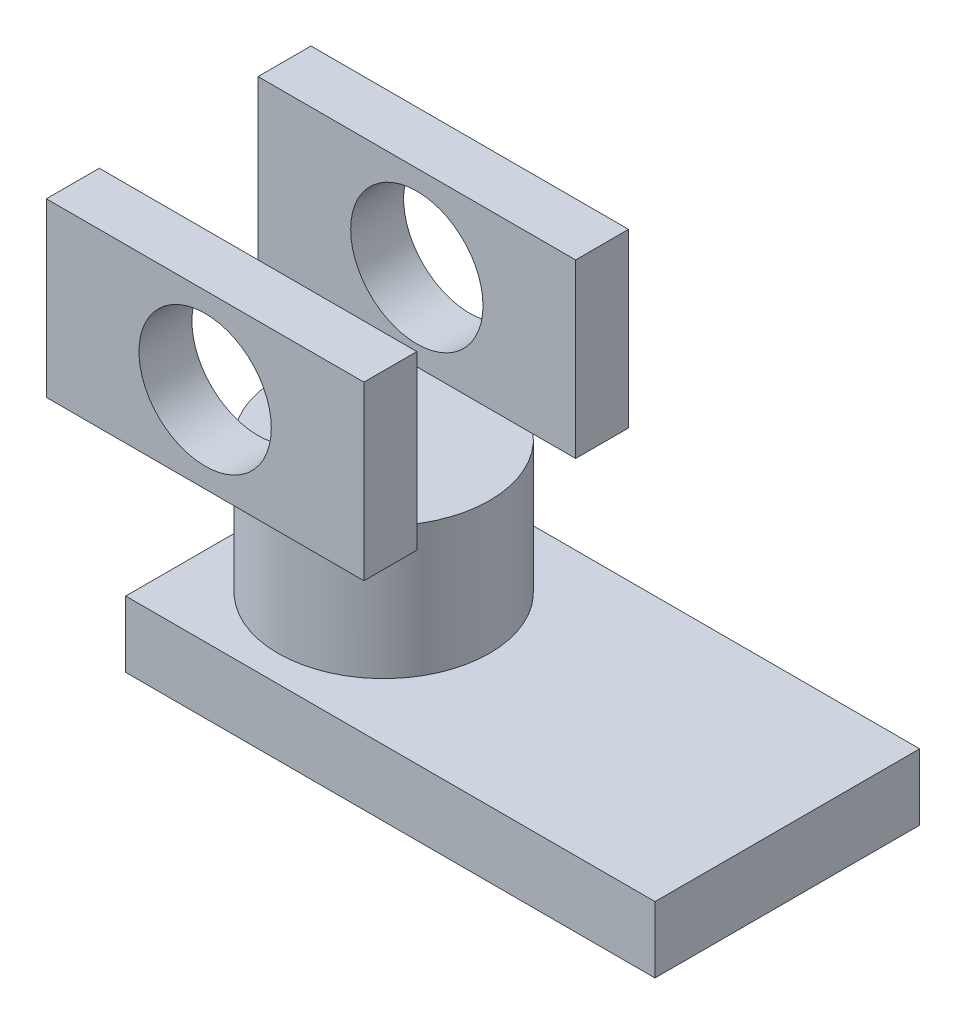
SolidWorks part; units mm, degrees
ref_plane "Front Plane" through (0, 0, 0) normal (0, 0, 1) x (1, 0, 0)
ref_plane "Top Plane" through (0, 0, 0) normal (0, 1, 0) x (1, 0, 0)
ref_plane "Right Plane" through (0, 0, 0) normal (1, 0, 0) x (0, 0, -1)
sketch "Sketch1" plane through (0, 0, 0) normal (0, 1, 0) x (1, 0, 0)
  line L0 (0, 0) -> (0, 20)
  line L1 (0, 20) -> (40, 20)
  line L2 (0, 0) -> (40, 0)
  line L3 (40, 0) -> (40, 20)
extrude "Boss-Extrude1" add sketch "Sketch1" along normal blind 5
sketch "Sketch2" plane through (0, 5, 0) normal (0, 1, 0) x (1, 0, 0)
  line L0 (0, 10) -> (9.5, 10)
  line L1 (0, 20) -> (0, 0) construction
  circle A0 centre (9.5, 10) radius 8
extrude "Boss-Extrude2" add sketch "Sketch2" along normal blind 10
sketch "Sketch4" plane through (0, 0, 0) normal (0, 0, 1) x (1, 0, 0)
  line L0 (0, 5) -> (0, 15)
  line L1 (0, 15) -> (17.5, 15)
  line L2 (17.5, 15) -> (17.5, 5)
  line L3 (1.5, 5) -> (1.5, 15)
  line L4 (1.5, 15) -> (1.5, 5) construction
  line L5 (17.5, 15) -> (18, 15)
  line L6 (18, 15) -> (18, 28)
  line L7 (18, 28) -> (-6, 28)
  line L8 (-6, 28) -> (-6, 15)
  line L9 (-6, 15) -> (17.5, 15)
extrude "Boss-Extrude3" add sketch "Sketch4" against normal through all contours L8 L9 L1 L5 L6 L7
sketch "Sketch5" plane through (18, 0, 0) normal (1, 0, 0) x (0, 0, -1)
  line L0 (10, 15) -> (16, 15)
  line L1 (20, 15) -> (0, 15) construction
  line L2 (16, 15) -> (16, 28)
  line L3 (20, 28) -> (0, 28) construction
  line L4 (16, 28) -> (4, 28)
  line L5 (4, 28) -> (4, 15)
  line L6 (4, 15) -> (10, 15)
extrude "Cut-Extrude1" cut sketch "Sketch5" against normal through all contours L6 L0 L2 L4 L5
sketch "Sketch6" plane through (0, 0, 0) normal (0, 0, 1) x (1, 0, 0)
  line L0 (18, 15) -> (18, 21.5)
  line L1 (18, 15) -> (18, 28) construction
  line L2 (18, 21.5) -> (6, 21.5)
  circle A0 centre (6, 21.5) radius 5
extrude "Cut-Extrude2" cut sketch "Sketch6" against normal through all
